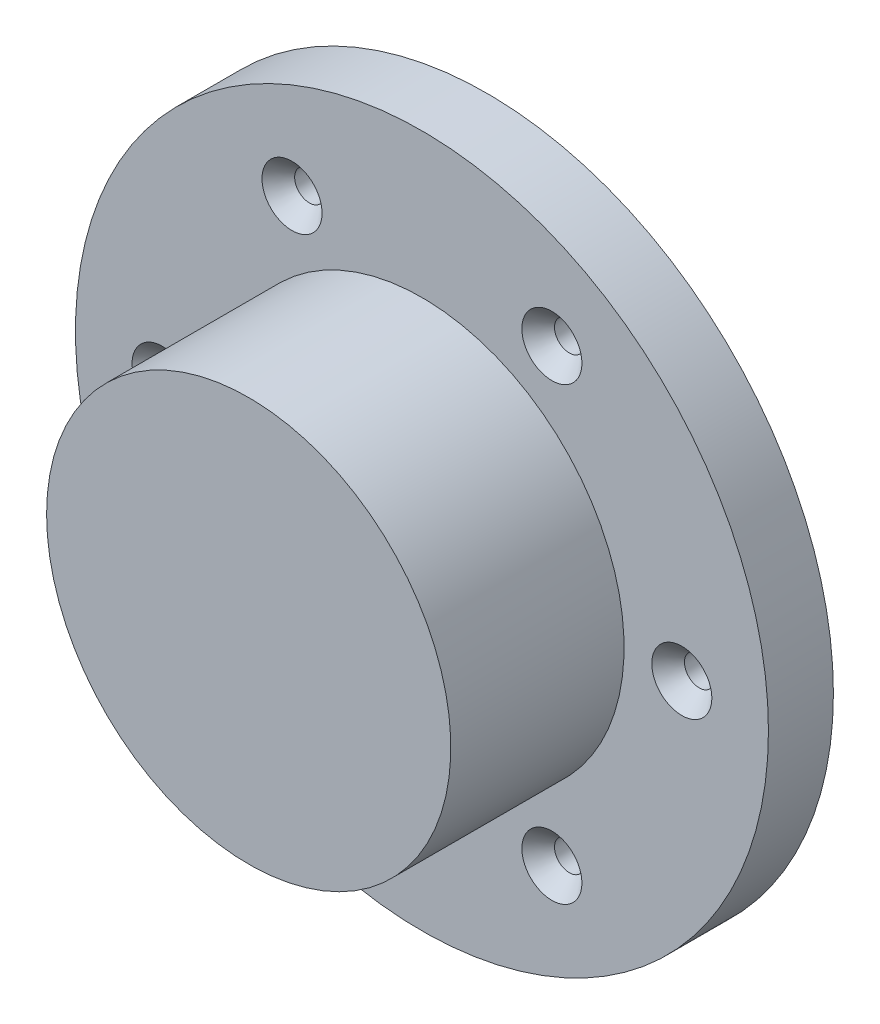
SolidWorks part; units mm, degrees
ref_plane "Front Plane" through (0, 0, 0) normal (0, 0, 1) x (1, 0, 0)
ref_plane "Top Plane" through (0, 0, 0) normal (0, 1, 0) x (1, 0, 0)
ref_plane "Right Plane" through (0, 0, 0) normal (1, 0, 0) x (0, 0, -1)
sketch "Sketch1" plane through (0, 0, 0) normal (0, 0, 1) x (1, 0, 0)
  line L0 (0, 0) -> (-28.575, 0) construction
  circle A0 centre (0, 0) radius 38.1
  circle A1 centre (0, 0) radius 28.575 construction
  point P18 (0, 0)
  dimension "D1" = 57.15
  dimension "D4" = 76.2
extrude "Boss-Extrude1" add sketch "Sketch1" along normal blind 7.1437
sketch "Sketch3" plane through (0, 0, 7.1437) normal (0, 0, 1) x (1, 0, 0)
  circle A0 centre (0, 0) radius 22.225
  dimension "D1" = 44.45
sketch "Sketch4" plane through (0, 0, 0) normal (0, 0, -1) x (-1, 0, 0)
  circle A0 centre (0, 0) radius 28.575 construction
  circle A2 centre (0, 0) radius 28.575 construction
  circle A4 centre (0, 0) radius 28.575 construction
  circle A6 centre (0, 0) radius 28.575 construction
  circle A8 centre (0, 0) radius 28.575 construction
  circle A10 centre (0, 0) radius 28.575 construction
  circle A12 centre (0, 0) radius 38.1 construction
  point P3 (-14.2875, 24.7467)
  point P4 (14.2875, 24.7467)
  point P6 (-28.575, 0)
  point P9 (28.575, 0)
  point P10 (14.2875, -24.7467)
  point P12 (-14.2875, -24.7467)
  point P13 (0, 0)
  point P23 (0, 0)
  dimension "D1" = 57.15
  dimension "D2" = 6
  dimension "D3" = 6
extrude "Boss-Extrude2" add sketch "Sketch3" along normal blind 19.05 separate body
sketch "Sketch10" plane through (0, 0, 7.1437) normal (0, 0, 1) x (1, 0, 0)
  point P0 (-28.575, 0)
  point P3 (-14.2875, 24.7467)
  point P6 (14.2875, 24.7467)
  point P9 (28.575, 0)
  point P12 (14.2875, -24.7467)
  point P15 (-14.2875, -24.7467)
hole_wizard "CSK for #4 Flat Head Machine Screw1" positions "Sketch10" profile "Sketch9" countersink size "#4" standard "ANSI Inch" end condition through all
sketch "Sketch9" plane through (-28.575, 0, 7.1437) normal (1, 0, 0) x (0, -1, 0)
  line L0 (0, 0) -> (0, 7.1437)
  line L1 (0, 7.1437) -> (1.6319, 7.1437)
  line L2 (1.6319, 7.1437) -> (1.6319, 1.9212)
  line L3 (1.6319, 1.9212) -> (3.302, 0)
  line L5 (3.302, 0) -> (0, 0)
  line L6 (-1.6319, 1.9212) -> (-3.302, 0) construction
  line L11 (0, -6.35) -> (0, 107.95) construction
  dimension "Thru Hole Dia." = 3.2639
  dimension "Thru Hole Depth" = 7.1437
  dimension "Near C'Sink Dia." = 6.604
  dimension "Near C'Sink Angle" = 82
sketch "Sketch11" plane through (0, 0, 0) normal (0, 0, -1) x (-1, 0, 0)
  circle A0 centre (0, 0) radius 17.4625
  dimension "D1" = 34.925
extrude "Cut-Extrude1" cut sketch "Sketch11" against normal blind 7.1437
